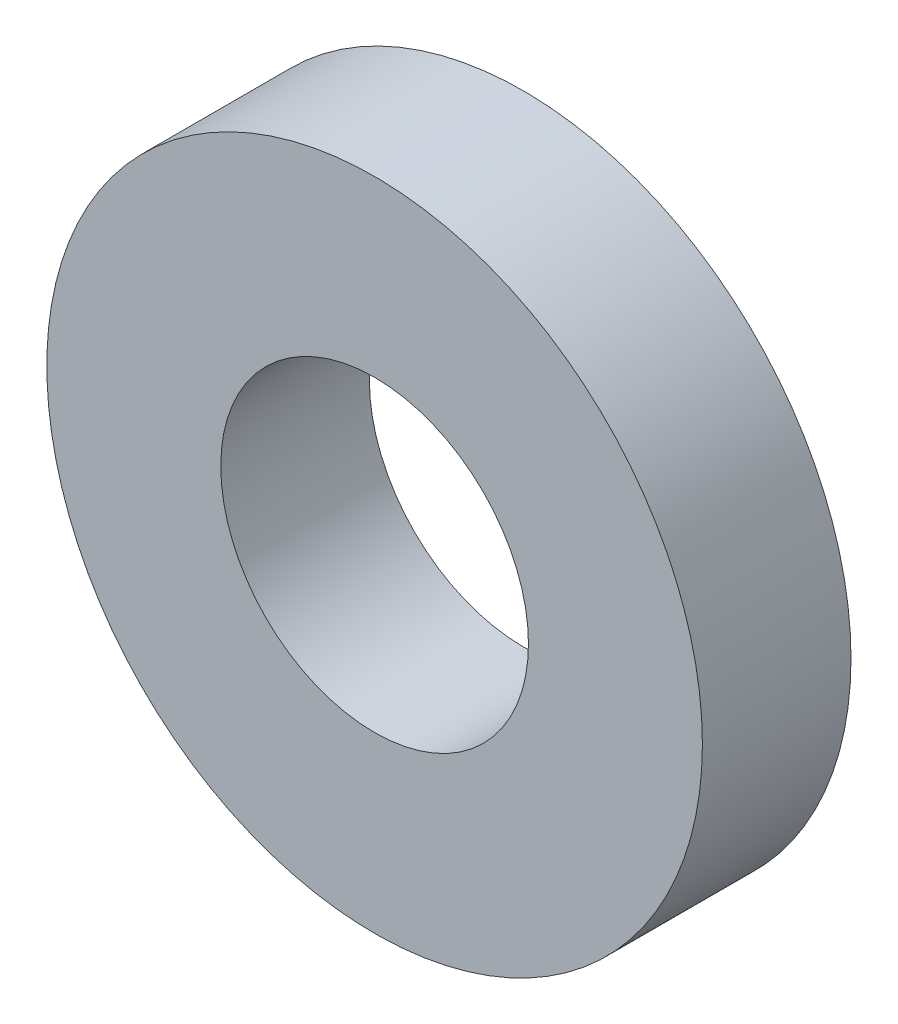
SolidWorks part; units mm, degrees
ref_plane "Ön Düzlem" through (0, 0, 0) normal (0, 0, 1) x (1, 0, 0)
ref_plane "Üst Düzlem" through (0, 0, 0) normal (0, 1, 0) x (1, 0, 0)
ref_plane "Sağ Düzlem" through (0, 0, 0) normal (1, 0, 0) x (0, 0, -1)
sketch "Çizim1" plane through (0, 0, 0) normal (0, 0, 1) x (1, 0, 0)
  circle A0 centre (0, 0) radius 17.6
  circle A1 centre (0, 0) radius 37.5
  dimension "D1" = 35.2
  dimension "D2" = 75
extrude "Yükseklik-Ekstrüzyon1" add sketch "Çizim1" along normal mid plane 17
